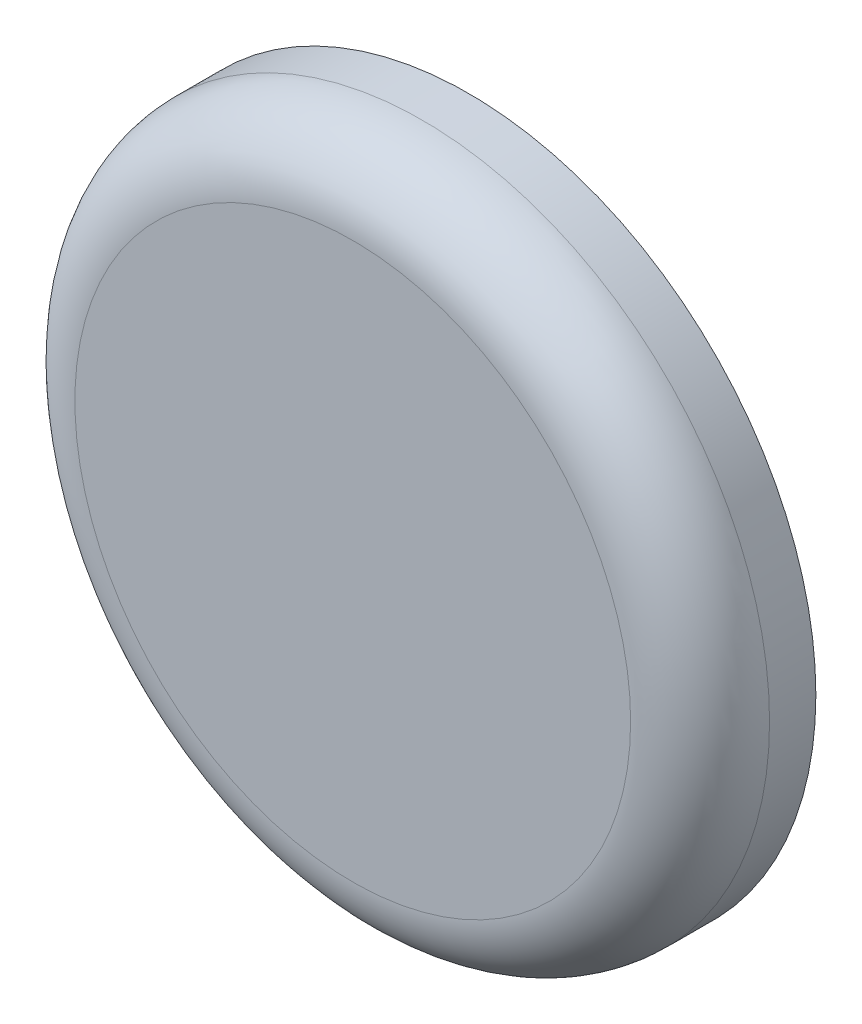
SolidWorks part; units mm, degrees
ref_plane "Front Plane" through (0, 0, 0) normal (0, 0, 1) x (1, 0, 0)
ref_plane "Top Plane" through (0, 0, 0) normal (0, 1, 0) x (1, 0, 0)
ref_plane "Right Plane" through (0, 0, 0) normal (1, 0, 0) x (0, 0, -1)
sketch "Sketch1" plane through (0, 0, 0) normal (0, 0, 1) x (1, 0, 0)
  circle A0 centre (0, 0) radius 15
extrude "Boss-Extrude1" add sketch "Sketch1" along normal blind 5
fillet "Fillet1" radius 3 1 edges at (15, 0, 5)
sketch "Sketch2" plane through (0, 0, 0) normal (0, 0, -1) x (-1, 0, 0)
  circle A0 centre (0, 0) radius 1.8
extrude "Cut-Extrude1" cut sketch "Sketch2" against normal blind 2.2 contours A0
